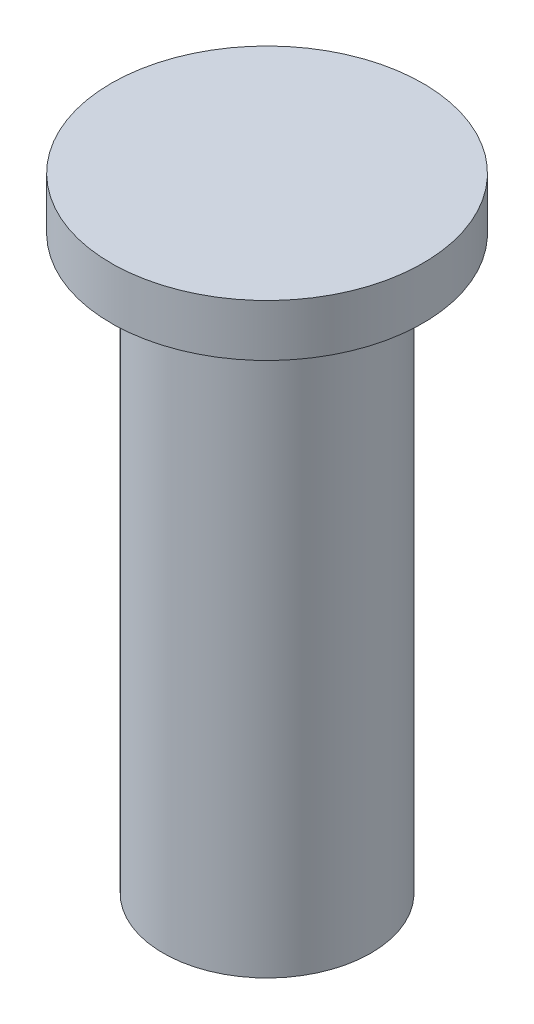
SolidWorks part; units mm, degrees
ref_plane "Alzado" through (0, 0, 0) normal (0, 0, 1) x (1, 0, 0)
ref_plane "Planta" through (0, 0, 0) normal (0, 1, 0) x (1, 0, 0)
ref_plane "Vista lateral" through (0, 0, 0) normal (1, 0, 0) x (0, 0, -1)
sketch "Croquis1" plane through (0, 0, 0) normal (0, 0, 1) x (1, 0, 0)
  line L0 (0, 0) -> (2, 0)
  line L1 (2, 0) -> (2, 11)
  line L2 (2, 11) -> (3, 11)
  line L3 (3, 11) -> (3, 12)
  line L4 (3, 12) -> (0, 12)
  line L5 (0, 12) -> (0, 0)
  dimension "D1" = 3
  dimension "D2" = 1
  dimension "D3" = 2
  dimension "D4" = 11
revolve "Revolución1" add sketch "Croquis1" angle 360 about L5
